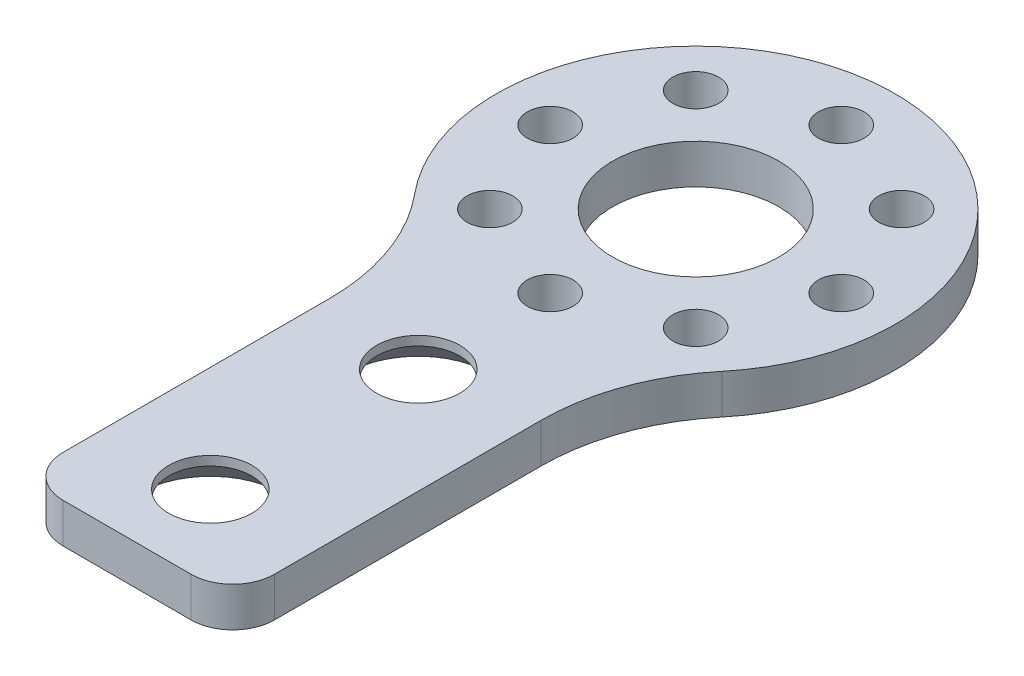
SolidWorks part; units mm, degrees
material "1060 Alloy"
ref_plane "Front Plane" through (0, 0, 0) normal (0, 0, 1) x (1, 0, 0)
ref_plane "Top Plane" through (0, 0, 0) normal (0, 1, 0) x (1, 0, 0)
ref_plane "Right Plane" through (0, 0, 0) normal (1, 0, 0) x (0, 0, -1)
sketch "Sketch1" plane through (0, 0, 0) normal (0, 1, 0) x (1, 0, 0)
  line L0 (-12.7, -68.3644) -> (12.7, -68.3644)
  line L1 (12.7, -68.3644) -> (12.7, -20.3644)
  line L2 (-12.7, -68.3644) -> (-12.7, -20.3644)
  arc A0 (12.7, -20.3644) -> (-12.7, -20.3644) centre (0, 0) ccw
  point P5 (0, -68.3644)
  dimension "D2" = 48
  dimension "D1" = 25.4
  dimension "D3" = 48
extrude "Boss-Extrude1" add sketch "Sketch1" along normal blind 4.7625 contours A0 L2 L0 L1
sketch "Sketch2" plane through (0, 0, 0) normal (0, -1, 0) x (1, 0, 0)
  circle A0 centre (0, 0) radius 17.5 construction
  point P3 (17.5, 0)
  point P6 (12.3744, -12.3744)
  point P7 (0, -17.5)
  point P8 (-12.3744, -12.3744)
  point P9 (-17.5, 0)
  point P10 (-12.3744, 12.3744)
  point P11 (0, 17.5)
  point P12 (12.3744, 12.3744)
  point P13 (0, 0)
  dimension "D2" = 35
  dimension "D1" = 8
hole_wizard "M5 Clearance Hole1" positions "Sketch3" profile "Sketch4" hole size "M5" standard "ANSI Metric" end condition through all
sketch "Sketch3" plane through (0, 0, 0) normal (0, -1, 0) x (-1, 0, 0)
  point P0 (0, 17.5)
  point P3 (12.3744, 12.3744)
  point P6 (17.5, 0)
  point P9 (12.3744, -12.3744)
  point P12 (0, -17.5)
  point P15 (-12.3744, -12.3744)
  point P18 (-17.5, 0)
  point P21 (-12.3744, 12.3744)
sketch "Sketch4" plane through (0, 0, -17.5) normal (1, 0, 0) x (0, 0, -1)
  line L0 (0, 0) -> (0, 4.7625)
  line L1 (0, 4.7625) -> (2.75, 4.7625)
  line L2 (2.75, 4.7625) -> (2.75, 0.025)
  line L3 (2.75, 0.025) -> (2.775, 0)
  line L5 (2.775, 0) -> (0, 0)
  line L6 (-2.75, 0.025) -> (-2.775, 0) construction
  line L11 (0, -6.35) -> (0, 107.95) construction
  dimension "Thru Hole Dia." = 5.5
  dimension "Thru Hole Depth" = 4.7625
  dimension "Near C'Sink Dia." = 5.55
  dimension "Near C'Sink Angle" = 90
sketch "Sketch5" plane through (0, 0, 0) normal (0, -1, 0) x (1, 0, 0)
  circle A0 centre (0, 0) radius 10
  dimension "D1" = 20
extrude "Cut-Extrude1" cut sketch "Sketch5" against normal through all
sketch "Sketch6" plane through (0, 0, 0) normal (0, -1, 0) x (1, 0, 0)
  line L0 (0, 68.3644) -> (0, 33.3644) construction
  line L1 (-12.7, 68.3644) -> (12.7, 68.3644) construction
  point P5 (0, 58.3644)
  dimension "D1" = 25
  dimension "D2" = 10
hole_wizard "CSK for M8 Flat Head Machine Screw1" positions "Sketch7" profile "Sketch8" countersink size "M8" standard "ANSI Metric" end condition through all
sketch "Sketch7" plane through (0, 0, 0) normal (0, -1, 0) x (-1, 0, 0)
  point P0 (0, -33.3644)
  point P3 (0, -58.3644)
sketch "Sketch8" plane through (0, 0, 33.3644) normal (1, 0, 0) x (0, 0, -1)
  line L0 (0, 0) -> (0, 4.7625)
  line L1 (0, 4.7625) -> (5, 4.7625)
  line L2 (5, 4.7625) -> (5, 3.65)
  line L3 (5, 3.65) -> (8.65, 0)
  line L5 (8.65, 0) -> (0, 0)
  line L6 (-5, 3.65) -> (-8.65, 0) construction
  line L11 (0, -6.35) -> (0, 107.95) construction
  dimension "Thru Hole Dia." = 10
  dimension "Thru Hole Depth" = 4.7625
  dimension "Near C'Sink Dia." = 17.3
  dimension "Near C'Sink Angle" = 90
fillet "Fillet1" radius 25 2 edges at (-12.7, 2.3813, 20.3644) (12.7, 2.3813, 20.3644)
fillet "Fillet2" radius 5 2 edges at (12.7, 2.3813, 68.3644) (-12.7, 2.3813, 68.3644)
